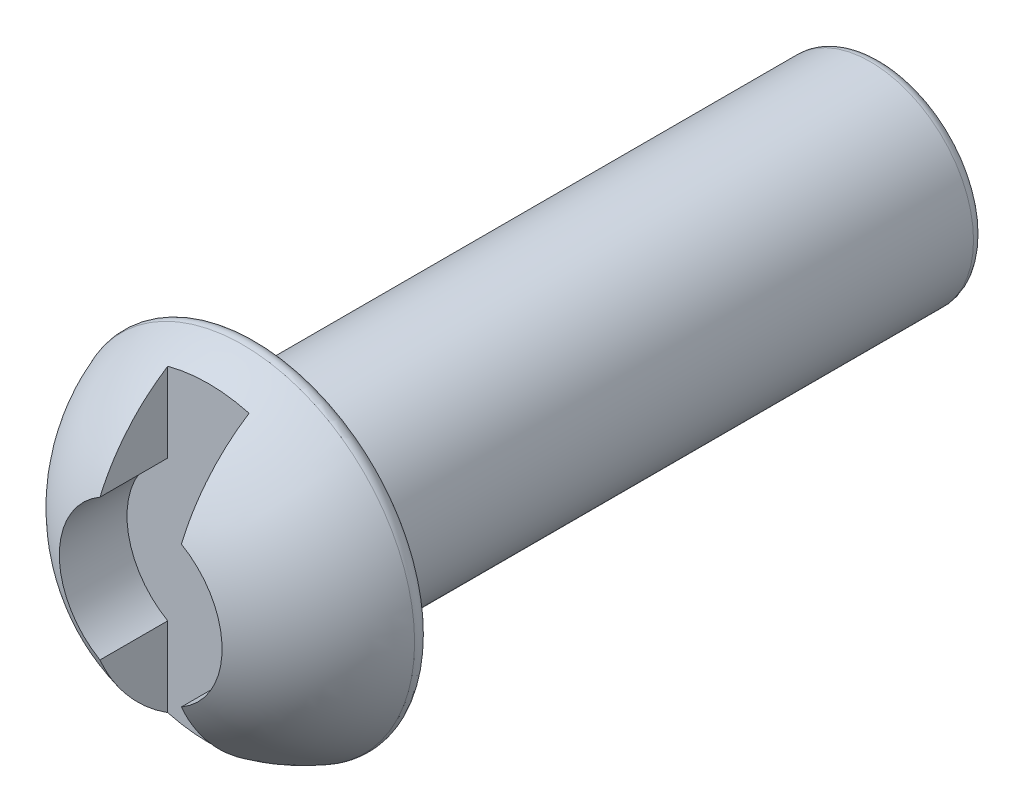
SolidWorks part; units mm, degrees
ref_plane "Front Plane" through (0, 0, 0) normal (0, 0, 1) x (1, 0, 0)
ref_plane "Top Plane" through (0, 0, 0) normal (0, 1, 0) x (1, 0, 0)
ref_plane "Right Plane" through (0, 0, 0) normal (1, 0, 0) x (0, 0, -1)
sketch "Sketch1" plane through (0, 0, 0) normal (1, 0, 0) x (0, 0, -1)
  line L0 (0, 0) -> (7, 0)
  line L1 (7, 0) -> (7, 0.95)
  line L2 (7, 0.95) -> (1.25, 0.95)
  line L3 (1.25, 0.95) -> (1.25, 1.625)
  line L4 (7, 0.475) -> (3.024, 0.475) construction
  arc A0 (1.25, 1.625) -> (0, 0) centre (1.68, 0.001) ccw
  dimension "D1" = 7
  dimension "D4" = 1.625
  dimension "D5" = 1.68
  dimension "D2" = 0.95
  dimension "D3" = 1.25
revolve "Revolve1" add sketch "Sketch1" angle 360 about L0
sketch "Sketch2" plane through (0, 0, 0) normal (0, 0, 1) x (1, 0, 0)
  line L1 (-0.375, -2.0593) -> (0.375, -2.0593)
  line L2 (-0.375, -2.0593) -> (-0.375, -0.6495)
  line L3 (-0.375, 2.0593) -> (0.375, 2.0593)
  line L4 (0.375, -2.0593) -> (0.375, -0.6495)
  line L8 (-0.375, 0.6495) -> (-0.375, 2.0593)
  line L9 (0.375, 0.6495) -> (0.375, 2.0593)
  arc A0 (-0.375, 0.6495) -> (-0.375, -0.6495) centre (0, 0) ccw
  arc A1 (0.375, -0.6495) -> (0.375, 0.6495) centre (0, 0) ccw
  point P0 (0, 0)
  dimension "D2" = 1.5
  dimension "D1" = 0.75
extrude "Cut-Extrude1" cut sketch "Sketch2" against normal blind 0.8
fillet "Fillet1" radius 0.1 1 edges at (1.625, 0, -1.25)
fillet "Fillet2" radius 0.1 1 edges at (0.95, 0, -7)
